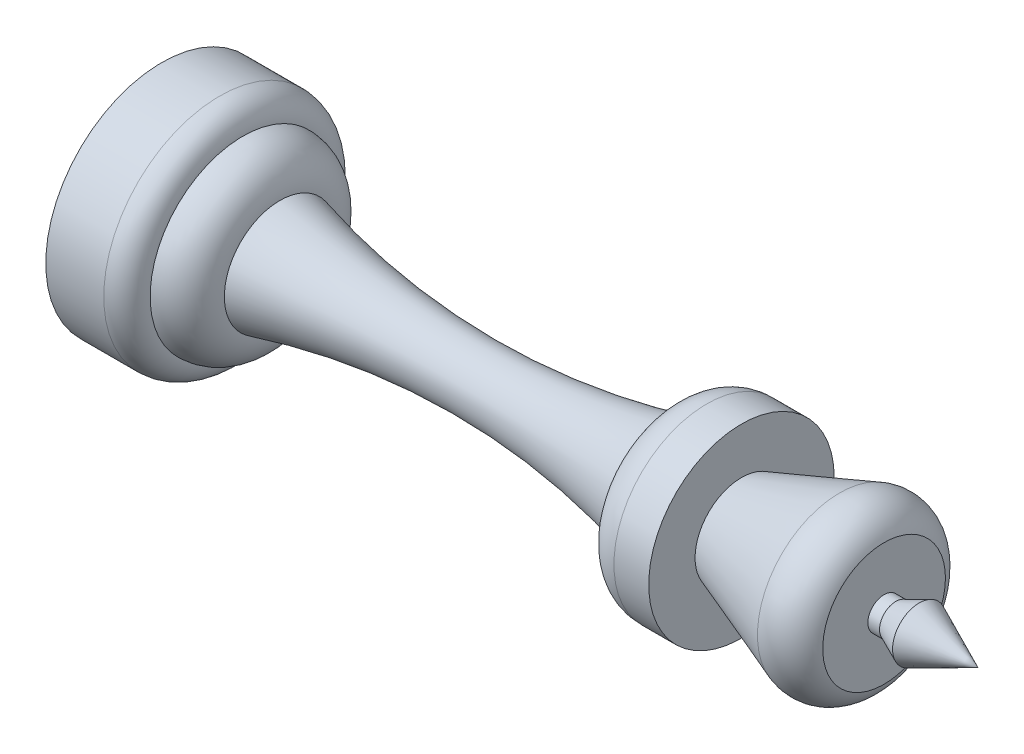
SolidWorks part; units mm, degrees
ref_plane "Спереди" through (0, 0, 0) normal (0, 0, 1) x (1, 0, 0)
ref_plane "Сверху" through (0, 0, 0) normal (0, 1, 0) x (1, 0, 0)
ref_plane "Справа" through (0, 0, 0) normal (1, 0, 0) x (0, 0, -1)
sketch "попа" plane through (0, 0, 0) normal (0, 1, 0) x (1, 0, 0)
  line L0 (0, 0) -> (0, 10)
  line L1 (0, 10) -> (5, 10)
  line L2 (5, 10) -> (5, 0)
  line L3 (-24.09, 0) -> (24.09, 0) construction
  line L4 (5, 0) -> (0, 0)
  line L5 (1, 0) -> (1, 5.25)
  line L6 (1, 5.25) -> (3.5, 5.25)
  line L7 (3.5, 5.25) -> (3.5, 0)
  line L8 (7, 0) -> (7, 8)
  line L9 (10.2, 4.8) -> (10.2, 0)
  line L10 (5, 0) -> (10.2, 0)
  arc A0 (5, 10) -> (7, 8) centre (5, 8) cw
  arc A1 (7, 8) -> (10.2, 4.8) centre (7, 4.8) cw
  dimension "D6" = 2
  dimension "D8" = 3.2
  dimension "D1" = 10
  dimension "D2" = 5
  dimension "D3" = 5.25
  dimension "D4" = 2.5
  dimension "D5" = 1
  dimension "D7" = 2
sketch "верх" plane through (0, 0, 0) normal (0, 1, 0) x (1, 0, 0)
  line L0 (10.2, 0) -> (43.8, 0)
  line L1 (43.8, 0) -> (43.8, 4.8)
  line L2 (47, 0) -> (47, 8)
  line L3 (-55, 0) -> (55, 0) construction
  line L4 (43.8, 0) -> (47, 0)
  line L5 (47, 8) -> (50, 8)
  line L6 (50, 8) -> (50, 0)
  line L7 (50, 0) -> (47, 0)
  line L8 (50, 4) -> (58.4572, 7.0782)
  line L9 (58.4572, 7.0782) -> (60.4308, 1.6559) construction
  line L10 (50, 0) -> (60.8, 0)
  line L11 (62.3, 5.2917) -> (62.3, 0)
  line L13 (10.2, 4.8) -> (10.2, 0)
  line L14 (62.3, 1.4) -> (63.3069, 1.4)
  line L15 (62.3, 0) -> (60.8, 0)
  line L16 (63.3069, 1.4) -> (65.3312, 2.3)
  line L17 (65.3312, 2.3) -> (70.4, 0)
  line L18 (62.3, 0) -> (70.4, 0)
  arc A0 (10.2, 4.8) -> (43.8, 4.8) centre (27, 67.5914) ccw
  arc A1 (43.8, 4.8) -> (47, 8) centre (47, 4.8) cw
  arc A2 (58.4572, 7.0782) -> (62.3, 5.2917) centre (59.4833, 4.2591) cw
  point P24 (71.1212, 0)
  point P28 (0, 0)
  point P29 (72.7666, 0)
  point P30 (71.1778, 0)
  dimension "D3" = 65
  dimension "D4" = 3.2
  dimension "D11" = 3
  dimension "D13" = 1.4
  dimension "D18" = 5.5663
  dimension "D17" = 2.2153
  dimension "D1" = 33.6
  dimension "D2" = 4.8
  dimension "D5" = 3.2
  dimension "D6" = 3
  dimension "D7" = 4
  dimension "D8" = 9
  dimension "D9" = 70
  dimension "D10" = 90
  dimension "D12" = 1.5
  dimension "D14" = 10.8
  dimension "D15" = 2.3
  dimension "D16" = 8.1
revolve "Повернуть1" add sketch "попа" angle 360 about L4
revolve "Повернуть2" add sketch "верх" angle 360 about L7
